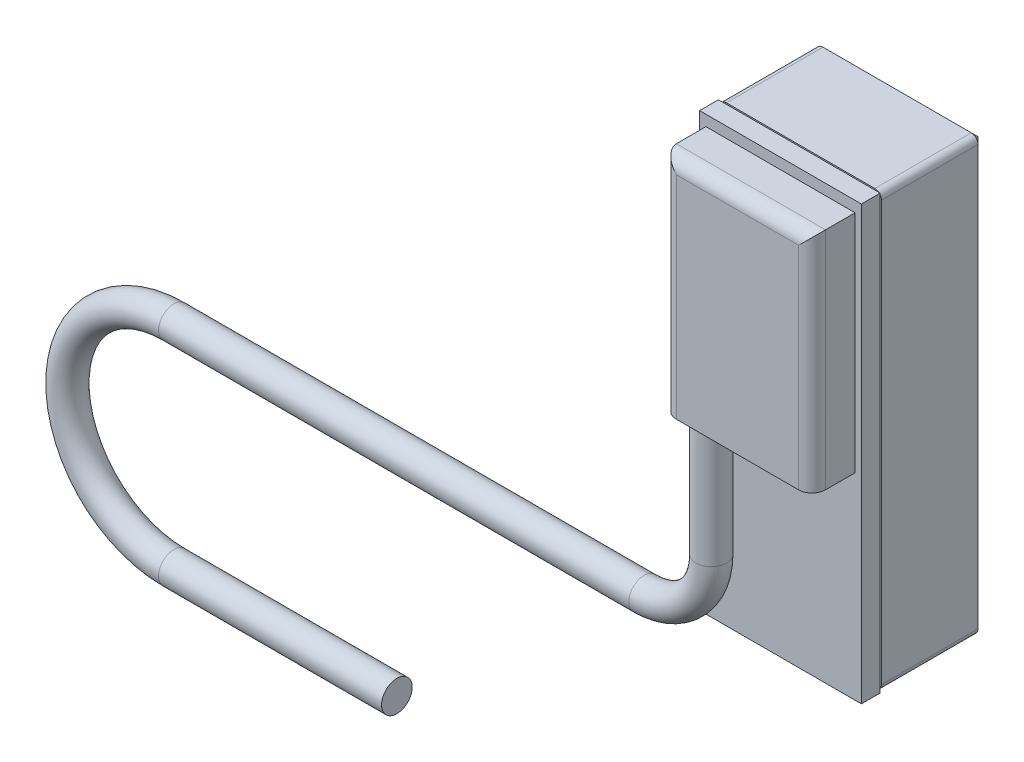
SolidWorks part; units mm, degrees
ref_plane "Спереди" through (0, 0, 0) normal (0, 0, 1) x (1, 0, 0)
ref_plane "Сверху" through (0, 0, 0) normal (0, 1, 0) x (1, 0, 0)
ref_plane "Справа" through (0, 0, 0) normal (1, 0, 0) x (0, 0, -1)
sketch "Эскиз1" plane through (0, 0, 0) normal (0, 0, 1) x (1, 0, 0)
  line L1 (-3.01, -8.055) -> (3.01, -8.055)
  line L2 (-3.01, -8.055) -> (-3.01, 8.055)
  line L3 (-3.01, 8.055) -> (3.01, 8.055)
  line L4 (3.01, -8.055) -> (3.01, 8.055)
  line L5 (-3.01, -8.055) -> (3.01, 8.055) construction
  line L6 (-3.01, 8.055) -> (3.01, -8.055) construction
  point P0 (0, 0)
  dimension "D1" = 6.02
  dimension "D2" = 16.11
extrude "Бобышка-Вытянуть1" add sketch "Эскиз1" along normal blind 3.84
sketch "Эскиз2" plane through (0, 0, 0) normal (0, 0, -1) x (-1, 0, 0)
  line L0 (-3.01, -8.055) -> (-3.01, 8.055) construction
  line L1 (-3.01, 8.055) -> (3.01, 8.055) construction
  circle A0 centre (-0.87, 0.795) radius 0.725
  dimension "D1" = 1.45
  dimension "D2" = 2.14
  dimension "D3" = 7.26
extrude "Бобышка-Вытянуть2" add sketch "Эскиз2" along normal blind 0.2
ref_plane "Плоскость1" through (0, 0, 3.89) normal (0, 0, 1) x (1, 0, 0)
sketch "Эскиз3" plane through (0, 0, 3.89) normal (0, 0, 1) x (1, 0, 0)
  line L1 (-3.01, -8.055) -> (3.01, -8.055)
  line L2 (-3.01, -8.055) -> (-3.01, 8.055)
  line L3 (-3.01, 8.055) -> (3.01, 8.055)
  line L4 (3.01, -8.055) -> (3.01, 8.055)
  line L5 (-3.01, -8.055) -> (3.01, 8.055) construction
  line L6 (-3.01, 8.055) -> (3.01, -8.055) construction
  point P0 (0, 0)
extrude "Бобышка-Вытянуть3" add sketch "Эскиз3" along normal blind 0.7 separate body
sketch "Эскиз4" plane through (0, 0, 4.59) normal (0, 0, 1) x (1, 0, 0)
  line L0 (3.01, 8.055) -> (-3.01, 8.055) construction
  line L1 (-2.775, -0.725) -> (2.775, -0.725)
  line L2 (-2.775, -0.725) -> (-2.775, 7.655)
  line L3 (-2.775, 7.655) -> (2.775, 7.655)
  line L4 (2.775, -0.725) -> (2.775, 7.655)
  line L5 (-2.775, -0.725) -> (2.775, 7.655) construction
  line L6 (-2.775, 7.655) -> (2.775, -0.725) construction
  point P0 (0, 3.465)
  point P6 (0, 0)
  dimension "D1" = 8.38
  dimension "D2" = 5.55
  dimension "D3" = 0.4
extrude "Бобышка-Вытянуть4" add sketch "Эскиз4" along normal blind 1.6
sketch "Эскиз5" plane through (0, -0.725, 0) normal (0, -1, 0) x (1, 0, 0)
  line L0 (-2.775, 5.39) -> (2.775, 5.39) construction
  line L1 (-2.775, 6.19) -> (-2.775, 4.59) construction
  line L2 (2.775, 6.19) -> (2.775, 4.59) construction
  circle A0 centre (-1.775, 5.39) radius 0.57
  dimension "D1" = 1.14
  dimension "D2" = 1
fillet "Скругление1" radius 0.5 3 edges at (-2.775, 3.465, 6.19) (0, 7.655, 6.19) (2.775, 3.465, 6.19)
fillet "Скругление2" radius 0.25 4 edges at (-3.01, -8.055, 1.92) (3.01, -8.055, 1.92) (3.01, 8.055, 1.92) (-3.01, 8.055, 1.92)
chamfer "Фаска1" distance 0.25 angle 45 8 edges at (3.01, 0, 0) (2.9368, 7.9818, 0) (2.9368, -7.9818, 0) (0, 8.055, 0) (0, -8.055, 0) (-2.9368, 7.9818, 0) (-2.9368, -7.9818, 0) (-3.01, 0, 0)
ref_plane "Плоскость2" through (0, 0, 5.39) normal (0, 0, 1) x (1, 0, 0)
sketch "Эскиз6" plane through (0, 0, 5.39) normal (0, 0, 1) x (1, 0, 0)
  line L0 (-1.775, -0.725) -> (-1.775, -5.225)
  line L1 (-4.275, -7.725) -> (-21.775, -7.725)
  line L2 (-21.775, -15.645) -> (-13.475, -15.645)
  arc A0 (-1.775, -5.225) -> (-4.275, -7.725) centre (-4.275, -5.225) cw
  arc A1 (-21.775, -7.725) -> (-21.775, -15.645) centre (-21.775, -11.685) ccw
  point P6 (-1.775, -7.725)
  dimension "D2" = 2.5
  dimension "D3" = 7.92
  dimension "D1" = 7
  dimension "D4" = 20
  dimension "D5" = 8.3
sweep "По траектории1" add profiles "Эскиз5" path "Эскиз6"
